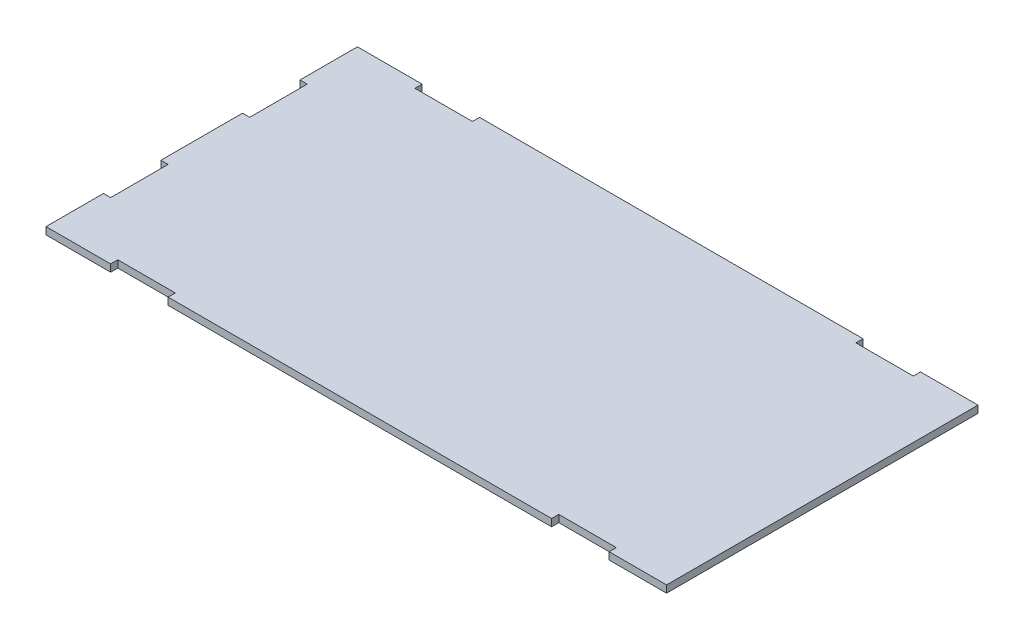
SolidWorks part; units mm, degrees
ref_plane "Front Plane" through (0, 0, 0) normal (0, 0, 1) x (1, 0, 0)
ref_plane "Top Plane" through (0, 0, 0) normal (0, 1, 0) x (1, 0, 0)
ref_plane "Right Plane" through (0, 0, 0) normal (1, 0, 0) x (0, 0, -1)
sketch "Sketch1" plane through (0, 0, 0) normal (0, 1, 0) x (1, 0, 0)
  line L0 (-133.985, 68.834) -> (-133.985, -68.834) construction
  line L1 (-137.16, 68.834) -> (-108.585, 68.834)
  line L2 (-137.16, 68.834) -> (-137.16, 43.434)
  line L3 (-137.16, -68.834) -> (-108.585, -68.834)
  line L4 (137.16, 68.834) -> (137.16, -68.834)
  line L5 (-137.16, -65.659) -> (137.16, -65.659) construction
  line L6 (-137.16, 65.659) -> (137.16, 65.659) construction
  line L7 (-108.585, 68.834) -> (-108.585, 65.659)
  line L8 (-108.585, 65.659) -> (-83.185, 65.659)
  line L9 (-83.185, 65.659) -> (-83.185, 68.834)
  line L10 (86.36, 68.834) -> (86.36, 65.659)
  line L11 (86.36, 65.659) -> (111.76, 65.659)
  line L12 (111.76, 65.659) -> (111.76, 68.834)
  line L13 (-108.585, -68.834) -> (-108.585, -65.659)
  line L14 (-108.585, -65.659) -> (-83.185, -65.659)
  line L15 (-83.185, -65.659) -> (-83.185, -68.834)
  line L16 (86.36, -68.834) -> (86.36, -65.659)
  line L17 (86.36, -65.659) -> (111.76, -65.659)
  line L18 (111.76, -65.659) -> (111.76, -68.834)
  line L19 (-137.16, -43.434) -> (-133.985, -43.434)
  line L20 (-133.985, -43.434) -> (-133.985, -18.034)
  line L21 (-133.985, -18.034) -> (-137.16, -18.034)
  line L22 (-137.16, 43.434) -> (-133.985, 43.434)
  line L23 (-133.985, 43.434) -> (-133.985, 18.034)
  line L24 (-133.985, 18.034) -> (-137.16, 18.034)
  line L25 (-83.185, 68.834) -> (86.36, 68.834)
  line L26 (-137.16, 18.034) -> (-137.16, -18.034)
  line L27 (-137.16, -43.434) -> (-137.16, -68.834)
  line L28 (-83.185, -68.834) -> (86.36, -68.834)
  line L29 (111.76, -68.834) -> (137.16, -68.834)
  line L30 (111.76, 68.834) -> (137.16, 68.834)
  dimension "D1" = 137.668
  dimension "D2" = 274.32
  dimension "D3" = 3.175
  dimension "D4" = 3.175
  dimension "D5" = 3.175
  dimension "D6" = 25.4
  dimension "D7" = 25.4
  dimension "D8" = 25.4
  dimension "D9" = 25.4
  dimension "D10" = 25.4
  dimension "D11" = 25.4
  dimension "D12" = 25.4
  dimension "D13" = 25.4
  dimension "D14" = 25.4
  dimension "D15" = 25.4
  dimension "D16" = 25.4
  dimension "D17" = 25.4
extrude "Boss-Extrude1" add sketch "Sketch1" along normal blind 3.175
